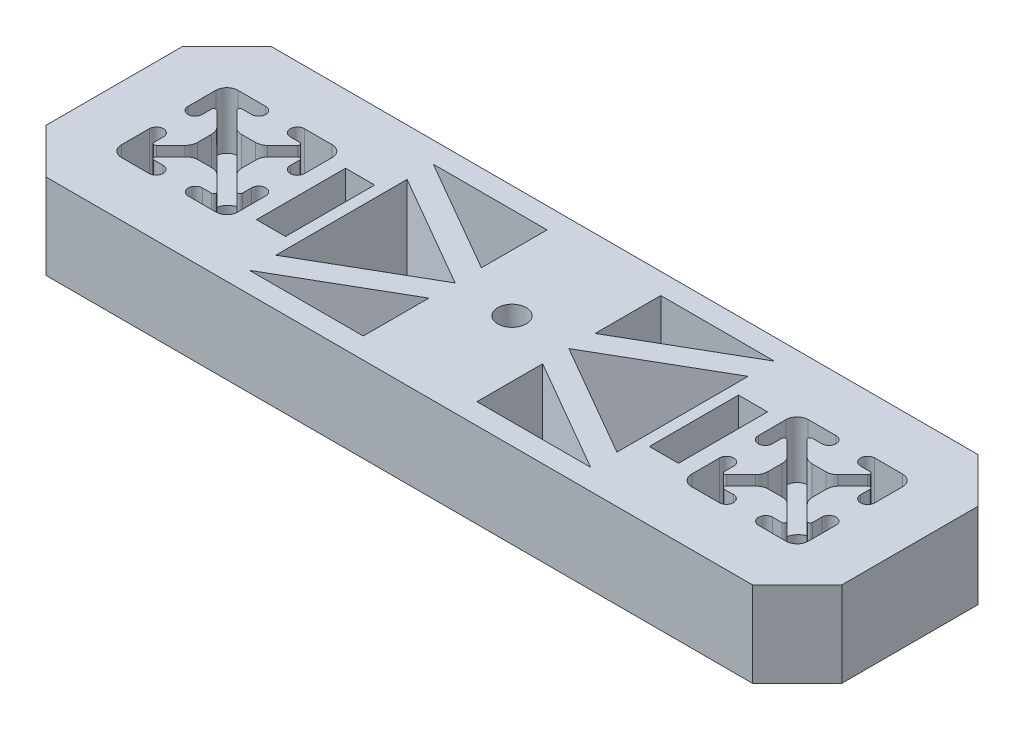
SolidWorks part; units mm, degrees
ref_plane "Front" through (0, 0, 0) normal (0, 0, 1) x (1, 0, 0)
ref_plane "Top" through (0, 0, 0) normal (0, 1, 0) x (1, 0, 0)
ref_plane "Right" through (0, 0, 0) normal (1, 0, 0) x (0, 0, -1)
sketch "Sketch1" plane through (0, 0, 0) normal (0, 1, 0) x (1, 0, 0)
  line L1 (0, 0) -> (177.8, 0)
  line L2 (0, 0) -> (0, 50.4)
  line L3 (0, 50.4) -> (177.8, 50.4)
  line L4 (177.8, 0) -> (177.8, 50.4)
  dimension "D1" = 177.8
  dimension "D2" = 50.4
extrude "Boss-Extrude1" add sketch "Sketch1" along normal blind 6.35
sketch "Sketch2" plane through (0, 6.35, 0) normal (0, 1, 0) x (1, 0, 0)
  line L0 (37.6996, 29.52) -> (37.6996, 35.7372) construction
  line L1 (35.7368, 37.7) -> (29.5196, 37.7) construction
  line L2 (29.5196, 35.56) -> (31.619, 35.56) construction
  line L3 (32.3326, 33.8353) -> (28.9966, 30.504) construction
  line L4 (26.7566, 29.5771) -> (23.643, 29.5771) construction
  line L5 (21.403, 30.504) -> (18.067, 33.8353) construction
  line L6 (18.7806, 35.56) -> (20.88, 35.56) construction
  line L7 (20.88, 37.7) -> (14.6628, 37.7) construction
  line L8 (12.7, 35.7372) -> (12.7, 29.52) construction
  line L9 (14.84, 29.52) -> (14.84, 31.5965) construction
  line L10 (16.5637, 32.3112) -> (19.7659, 29.1135) construction
  line L11 (20.743, 26.7568) -> (20.743, 23.6432) construction
  line L12 (19.7659, 21.2865) -> (16.5637, 18.0888) construction
  line L13 (14.84, 18.8035) -> (14.84, 20.88) construction
  line L14 (12.7, 20.88) -> (12.7, 14.6628) construction
  line L15 (14.6628, 12.7) -> (20.8121, 12.7) construction
  line L16 (20.8121, 14.84) -> (18.7806, 14.84) construction
  line L17 (18.067, 16.5647) -> (21.403, 19.896) construction
  line L18 (23.643, 20.8229) -> (26.7566, 20.8229) construction
  line L19 (28.9966, 19.896) -> (32.3326, 16.5647) construction
  line L20 (31.619, 14.84) -> (29.5875, 14.84) construction
  line L21 (29.5875, 12.7) -> (35.7368, 12.7) construction
  line L22 (37.6996, 14.6628) -> (37.6996, 20.88) construction
  line L23 (35.5596, 20.88) -> (35.5596, 18.8035) construction
  line L24 (33.8359, 18.0888) -> (30.6337, 21.2865) construction
  line L25 (29.6566, 23.6432) -> (29.6566, 26.7568) construction
  line L26 (30.6337, 29.1135) -> (33.8359, 32.3112) construction
  line L27 (35.5596, 31.5965) -> (35.5596, 29.52) construction
  line L28 (0, 50.4) -> (0, 0) construction
  line L29 (177.8, 50.4) -> (0, 50.4) construction
  line L30 (0, 0) -> (177.8, 0) construction
  line L31 (88.9, 50.4) -> (88.9, 0) construction
  line L32 (142.2404, 31.5965) -> (142.2404, 29.52) construction
  line L33 (147.1663, 29.1135) -> (143.9641, 32.3112) construction
  line L34 (148.1434, 23.6432) -> (148.1434, 26.7568) construction
  line L35 (143.9641, 18.0888) -> (147.1663, 21.2865) construction
  line L36 (142.2404, 20.88) -> (142.2404, 18.8035) construction
  line L37 (140.1004, 14.6628) -> (140.1004, 20.88) construction
  line L38 (148.2125, 12.7) -> (142.0632, 12.7) construction
  line L39 (146.181, 14.84) -> (148.2125, 14.84) construction
  line L40 (148.8034, 19.896) -> (145.4674, 16.5647) construction
  line L41 (154.157, 20.8229) -> (151.0434, 20.8229) construction
  line L42 (159.733, 16.5647) -> (156.397, 19.896) construction
  line L43 (156.9879, 14.84) -> (159.0194, 14.84) construction
  line L44 (163.1372, 12.7) -> (156.9879, 12.7) construction
  line L45 (165.1, 20.88) -> (165.1, 14.6628) construction
  line L46 (162.96, 18.8035) -> (162.96, 20.88) construction
  line L47 (158.0341, 21.2865) -> (161.2363, 18.0888) construction
  line L48 (157.057, 26.7568) -> (157.057, 23.6432) construction
  line L49 (161.2363, 32.3112) -> (158.0341, 29.1135) construction
  line L50 (162.96, 29.52) -> (162.96, 31.5965) construction
  line L51 (165.1, 35.7372) -> (165.1, 29.52) construction
  line L52 (156.92, 37.7) -> (163.1372, 37.7) construction
  line L53 (159.0194, 35.56) -> (156.92, 35.56) construction
  line L54 (156.397, 30.504) -> (159.733, 33.8353) construction
  line L55 (151.0434, 29.5771) -> (154.157, 29.5771) construction
  line L56 (145.4674, 33.8353) -> (148.8034, 30.504) construction
  line L57 (148.2804, 35.56) -> (146.181, 35.56) construction
  line L58 (142.0632, 37.7) -> (148.2804, 37.7) construction
  line L59 (140.1004, 29.52) -> (140.1004, 35.7372) construction
  line L60 (38.2076, 29.52) -> (38.2076, 35.7372)
  line L62 (0, 50.4) -> (0, 0)
  line L63 (0, 0) -> (177.8, 0)
  line L64 (177.8, 50.4) -> (177.8, 0)
  line L65 (35.7368, 38.208) -> (29.5196, 38.208)
  line L66 (29.5196, 35.052) -> (31.619, 35.052)
  line L67 (31.9737, 34.1948) -> (28.6376, 30.8635)
  line L68 (26.7566, 30.0851) -> (23.643, 30.0851)
  line L69 (21.762, 30.8635) -> (18.4259, 34.1948)
  line L70 (18.7806, 35.052) -> (20.88, 35.052)
  line L71 (20.88, 38.208) -> (14.6628, 38.208)
  line L72 (12.192, 35.7372) -> (12.192, 29.52)
  line L73 (15.348, 29.52) -> (15.348, 31.5965)
  line L74 (16.2047, 31.9517) -> (19.4069, 28.7541)
  line L75 (20.235, 26.7568) -> (20.235, 23.6432)
  line L76 (19.4069, 21.6459) -> (16.2047, 18.4483)
  line L77 (15.348, 18.8035) -> (15.348, 20.88)
  line L78 (12.192, 20.88) -> (12.192, 14.6628)
  line L79 (14.6628, 12.192) -> (20.8121, 12.192)
  line L80 (20.8121, 15.348) -> (18.7806, 15.348)
  line L81 (18.4259, 16.2052) -> (21.762, 19.5365)
  line L82 (23.643, 20.3149) -> (26.7566, 20.3149)
  line L83 (28.6376, 19.5365) -> (31.9737, 16.2052)
  line L84 (31.619, 15.348) -> (29.5875, 15.348)
  line L85 (29.5875, 12.192) -> (35.7368, 12.192)
  line L86 (38.2076, 14.6628) -> (38.2076, 20.88)
  line L87 (35.0516, 20.88) -> (35.0516, 18.8035)
  line L88 (34.1949, 18.4483) -> (30.9927, 21.6459)
  line L89 (30.1646, 23.6432) -> (30.1646, 26.7568)
  line L90 (30.9927, 28.7541) -> (34.1949, 31.9517)
  line L91 (35.0516, 31.5965) -> (35.0516, 29.52)
  line L92 (142.7484, 31.5965) -> (142.7484, 29.52)
  line L93 (139.5924, 29.52) -> (139.5924, 35.7372)
  line L94 (142.0632, 38.208) -> (148.2804, 38.208)
  line L95 (148.2804, 35.052) -> (146.181, 35.052)
  line L96 (145.8263, 34.1948) -> (149.1624, 30.8635)
  line L97 (151.0434, 30.0851) -> (154.157, 30.0851)
  line L98 (156.038, 30.8635) -> (159.3741, 34.1948)
  line L99 (159.0194, 35.052) -> (156.92, 35.052)
  line L100 (156.92, 38.208) -> (163.1372, 38.208)
  line L101 (165.608, 35.7372) -> (165.608, 29.52)
  line L102 (162.452, 29.52) -> (162.452, 31.5965)
  line L103 (161.5953, 31.9517) -> (158.3931, 28.7541)
  line L104 (157.565, 26.7568) -> (157.565, 23.6432)
  line L105 (158.3931, 21.6459) -> (161.5953, 18.4483)
  line L106 (162.452, 18.8035) -> (162.452, 20.88)
  line L107 (165.608, 20.88) -> (165.608, 14.6628)
  line L108 (163.1372, 12.192) -> (156.9879, 12.192)
  line L109 (156.9879, 15.348) -> (159.0194, 15.348)
  line L110 (159.3741, 16.2052) -> (156.038, 19.5365)
  line L111 (154.157, 20.3149) -> (151.0434, 20.3149)
  line L112 (149.1624, 19.5365) -> (145.8263, 16.2052)
  line L113 (146.181, 15.348) -> (148.2125, 15.348)
  line L114 (148.2125, 12.192) -> (142.0632, 12.192)
  line L115 (139.5924, 14.6628) -> (139.5924, 20.88)
  line L116 (142.7484, 20.88) -> (142.7484, 18.8035)
  line L117 (143.6051, 18.4483) -> (146.8073, 21.6459)
  line L118 (147.6354, 23.6432) -> (147.6354, 26.7568)
  line L119 (146.8073, 28.7541) -> (143.6051, 31.9517)
  line L120 (177.8, 50.4) -> (0, 50.4)
  arc A1 (37.6996, 35.7372) -> (35.7368, 37.7) centre (35.7368, 35.7372) ccw construction
  arc A2 (29.5196, 37.7) -> (29.5196, 35.56) centre (29.5196, 36.63) ccw construction
  arc A3 (31.619, 35.56) -> (32.3326, 33.8353) centre (31.619, 34.55) cw construction
  arc A4 (28.9966, 30.504) -> (26.7566, 29.5771) centre (26.7566, 32.7471) cw construction
  arc A5 (23.643, 29.5771) -> (21.403, 30.504) centre (23.643, 32.7471) cw construction
  arc A6 (18.067, 33.8353) -> (18.7806, 35.56) centre (18.7806, 34.55) cw construction
  arc A7 (20.88, 35.56) -> (20.88, 37.7) centre (20.88, 36.63) ccw construction
  arc A8 (14.6628, 37.7) -> (12.7, 35.7372) centre (14.6628, 35.7372) ccw construction
  arc A9 (12.7, 29.52) -> (14.84, 29.52) centre (13.77, 29.52) ccw construction
  arc A10 (14.84, 31.5965) -> (16.5637, 32.3112) centre (15.85, 31.5965) cw construction
  arc A11 (19.7659, 29.1135) -> (20.743, 26.7568) centre (17.4126, 26.7568) cw construction
  arc A12 (20.743, 23.6432) -> (19.7659, 21.2865) centre (17.4126, 23.6432) cw construction
  arc A13 (16.5637, 18.0888) -> (14.84, 18.8035) centre (15.85, 18.8035) cw construction
  arc A14 (14.84, 20.88) -> (12.7, 20.88) centre (13.77, 20.88) ccw construction
  arc A15 (12.7, 14.6628) -> (14.6628, 12.7) centre (14.6628, 14.6628) ccw construction
  arc A16 (20.8121, 12.7) -> (20.8121, 14.84) centre (20.8121, 13.77) ccw construction
  arc A17 (18.7806, 14.84) -> (18.067, 16.5647) centre (18.7806, 15.85) cw construction
  arc A18 (21.403, 19.896) -> (23.643, 20.8229) centre (23.643, 17.6529) cw construction
  arc A19 (26.7566, 20.8229) -> (28.9966, 19.896) centre (26.7566, 17.6529) cw construction
  arc A20 (32.3326, 16.5647) -> (31.619, 14.84) centre (31.619, 15.85) cw construction
  arc A21 (29.5875, 14.84) -> (29.5875, 12.7) centre (29.5875, 13.77) ccw construction
  arc A22 (35.7368, 12.7) -> (37.6996, 14.6628) centre (35.7368, 14.6628) ccw construction
  arc A23 (37.6996, 20.88) -> (35.5596, 20.88) centre (36.6296, 20.88) ccw construction
  arc A24 (35.5596, 18.8035) -> (33.8359, 18.0888) centre (34.5496, 18.8035) cw construction
  arc A25 (30.6337, 21.2865) -> (29.6566, 23.6432) centre (32.987, 23.6432) cw construction
  arc A26 (29.6566, 26.7568) -> (30.6337, 29.1135) centre (32.987, 26.7568) cw construction
  arc A27 (33.8359, 32.3112) -> (35.5596, 31.5965) centre (34.5496, 31.5965) cw construction
  arc A28 (35.5596, 29.52) -> (37.6996, 29.52) centre (36.6296, 29.52) ccw construction
  arc A29 (142.2404, 29.52) -> (140.1004, 29.52) centre (141.1704, 29.52) cw construction
  arc A30 (143.9641, 32.3112) -> (142.2404, 31.5965) centre (143.2504, 31.5965) ccw construction
  arc A31 (148.1434, 26.7568) -> (147.1663, 29.1135) centre (144.813, 26.7568) ccw construction
  arc A32 (147.1663, 21.2865) -> (148.1434, 23.6432) centre (144.813, 23.6432) ccw construction
  arc A33 (142.2404, 18.8035) -> (143.9641, 18.0888) centre (143.2504, 18.8035) ccw construction
  arc A34 (140.1004, 20.88) -> (142.2404, 20.88) centre (141.1704, 20.88) cw construction
  arc A35 (142.0632, 12.7) -> (140.1004, 14.6628) centre (142.0632, 14.6628) cw construction
  arc A36 (148.2125, 14.84) -> (148.2125, 12.7) centre (148.2125, 13.77) cw construction
  arc A37 (145.4674, 16.5647) -> (146.181, 14.84) centre (146.181, 15.85) ccw construction
  arc A38 (151.0434, 20.8229) -> (148.8034, 19.896) centre (151.0434, 17.6529) ccw construction
  arc A39 (156.397, 19.896) -> (154.157, 20.8229) centre (154.157, 17.6529) ccw construction
  arc A40 (159.0194, 14.84) -> (159.733, 16.5647) centre (159.0194, 15.85) ccw construction
  arc A41 (156.9879, 12.7) -> (156.9879, 14.84) centre (156.9879, 13.77) cw construction
  arc A42 (165.1, 14.6628) -> (163.1372, 12.7) centre (163.1372, 14.6628) cw construction
  arc A43 (162.96, 20.88) -> (165.1, 20.88) centre (164.03, 20.88) cw construction
  arc A44 (161.2363, 18.0888) -> (162.96, 18.8035) centre (161.95, 18.8035) ccw construction
  arc A45 (157.057, 23.6432) -> (158.0341, 21.2865) centre (160.3874, 23.6432) ccw construction
  arc A46 (158.0341, 29.1135) -> (157.057, 26.7568) centre (160.3874, 26.7568) ccw construction
  arc A47 (162.96, 31.5965) -> (161.2363, 32.3112) centre (161.95, 31.5965) ccw construction
  arc A48 (165.1, 29.52) -> (162.96, 29.52) centre (164.03, 29.52) cw construction
  arc A49 (163.1372, 37.7) -> (165.1, 35.7372) centre (163.1372, 35.7372) cw construction
  arc A50 (156.92, 35.56) -> (156.92, 37.7) centre (156.92, 36.63) cw construction
  arc A51 (159.733, 33.8353) -> (159.0194, 35.56) centre (159.0194, 34.55) ccw construction
  arc A52 (154.157, 29.5771) -> (156.397, 30.504) centre (154.157, 32.7471) ccw construction
  arc A53 (148.8034, 30.504) -> (151.0434, 29.5771) centre (151.0434, 32.7471) ccw construction
  arc A54 (146.181, 35.56) -> (145.4674, 33.8353) centre (146.181, 34.55) ccw construction
  arc A55 (148.2804, 37.7) -> (148.2804, 35.56) centre (148.2804, 36.63) cw construction
  arc A56 (140.1004, 35.7372) -> (142.0632, 37.7) centre (142.0632, 35.7372) cw construction
  arc A58 (38.2076, 35.7372) -> (35.7368, 38.208) centre (35.7368, 35.7372) ccw
  arc A59 (29.5196, 38.208) -> (29.5196, 35.052) centre (29.5196, 36.63) ccw
  arc A60 (31.619, 35.052) -> (31.9737, 34.1948) centre (31.619, 34.55) cw
  arc A61 (28.6376, 30.8635) -> (26.7566, 30.0851) centre (26.7566, 32.7471) cw
  arc A62 (23.643, 30.0851) -> (21.762, 30.8635) centre (23.643, 32.7471) cw
  arc A63 (18.4259, 34.1948) -> (18.7806, 35.052) centre (18.7806, 34.55) cw
  arc A64 (20.88, 35.052) -> (20.88, 38.208) centre (20.88, 36.63) ccw
  arc A65 (14.6628, 38.208) -> (12.192, 35.7372) centre (14.6628, 35.7372) ccw
  arc A66 (12.192, 29.52) -> (15.348, 29.52) centre (13.77, 29.52) ccw
  arc A67 (15.348, 31.5965) -> (16.2047, 31.9517) centre (15.85, 31.5965) cw
  arc A68 (19.4069, 28.7541) -> (20.235, 26.7568) centre (17.4126, 26.7568) cw
  arc A69 (20.235, 23.6432) -> (19.4069, 21.6459) centre (17.4126, 23.6432) cw
  arc A70 (16.2047, 18.4483) -> (15.348, 18.8035) centre (15.85, 18.8035) cw
  arc A71 (15.348, 20.88) -> (12.192, 20.88) centre (13.77, 20.88) ccw
  arc A72 (12.192, 14.6628) -> (14.6628, 12.192) centre (14.6628, 14.6628) ccw
  arc A73 (20.8121, 12.192) -> (20.8121, 15.348) centre (20.8121, 13.77) ccw
  arc A74 (18.7806, 15.348) -> (18.4259, 16.2052) centre (18.7806, 15.85) cw
  arc A75 (21.762, 19.5365) -> (23.643, 20.3149) centre (23.643, 17.6529) cw
  arc A76 (26.7566, 20.3149) -> (28.6376, 19.5365) centre (26.7566, 17.6529) cw
  arc A77 (31.9737, 16.2052) -> (31.619, 15.348) centre (31.619, 15.85) cw
  arc A78 (29.5875, 15.348) -> (29.5875, 12.192) centre (29.5875, 13.77) ccw
  arc A79 (35.7368, 12.192) -> (38.2076, 14.6628) centre (35.7368, 14.6628) ccw
  arc A80 (38.2076, 20.88) -> (35.0516, 20.88) centre (36.6296, 20.88) ccw
  arc A81 (35.0516, 18.8035) -> (34.1949, 18.4483) centre (34.5496, 18.8035) cw
  arc A82 (30.9927, 21.6459) -> (30.1646, 23.6432) centre (32.987, 23.6432) cw
  arc A83 (30.1646, 26.7568) -> (30.9927, 28.7541) centre (32.987, 26.7568) cw
  arc A84 (34.1949, 31.9517) -> (35.0516, 31.5965) centre (34.5496, 31.5965) cw
  arc A85 (35.0516, 29.52) -> (38.2076, 29.52) centre (36.6296, 29.52) ccw
  arc A86 (142.7484, 29.52) -> (139.5924, 29.52) centre (141.1704, 29.52) cw
  arc A87 (139.5924, 35.7372) -> (142.0632, 38.208) centre (142.0632, 35.7372) cw
  arc A88 (148.2804, 38.208) -> (148.2804, 35.052) centre (148.2804, 36.63) cw
  arc A89 (146.181, 35.052) -> (145.8263, 34.1948) centre (146.181, 34.55) ccw
  arc A90 (149.1624, 30.8635) -> (151.0434, 30.0851) centre (151.0434, 32.7471) ccw
  arc A91 (154.157, 30.0851) -> (156.038, 30.8635) centre (154.157, 32.7471) ccw
  arc A92 (159.3741, 34.1948) -> (159.0194, 35.052) centre (159.0194, 34.55) ccw
  arc A93 (156.92, 35.052) -> (156.92, 38.208) centre (156.92, 36.63) cw
  arc A94 (163.1372, 38.208) -> (165.608, 35.7372) centre (163.1372, 35.7372) cw
  arc A95 (165.608, 29.52) -> (162.452, 29.52) centre (164.03, 29.52) cw
  arc A96 (162.452, 31.5965) -> (161.5953, 31.9517) centre (161.95, 31.5965) ccw
  arc A97 (158.3931, 28.7541) -> (157.565, 26.7568) centre (160.3874, 26.7568) ccw
  arc A98 (157.565, 23.6432) -> (158.3931, 21.6459) centre (160.3874, 23.6432) ccw
  arc A99 (161.5953, 18.4483) -> (162.452, 18.8035) centre (161.95, 18.8035) ccw
  arc A100 (162.452, 20.88) -> (165.608, 20.88) centre (164.03, 20.88) cw
  arc A101 (165.608, 14.6628) -> (163.1372, 12.192) centre (163.1372, 14.6628) cw
  arc A102 (156.9879, 12.192) -> (156.9879, 15.348) centre (156.9879, 13.77) cw
  arc A103 (159.0194, 15.348) -> (159.3741, 16.2052) centre (159.0194, 15.85) ccw
  arc A104 (156.038, 19.5365) -> (154.157, 20.3149) centre (154.157, 17.6529) ccw
  arc A105 (151.0434, 20.3149) -> (149.1624, 19.5365) centre (151.0434, 17.6529) ccw
  arc A106 (145.8263, 16.2052) -> (146.181, 15.348) centre (146.181, 15.85) ccw
  arc A107 (148.2125, 15.348) -> (148.2125, 12.192) centre (148.2125, 13.77) cw
  arc A108 (142.0632, 12.192) -> (139.5924, 14.6628) centre (142.0632, 14.6628) cw
  arc A109 (139.5924, 20.88) -> (142.7484, 20.88) centre (141.1704, 20.88) cw
  arc A110 (142.7484, 18.8035) -> (143.6051, 18.4483) centre (143.2504, 18.8035) ccw
  arc A111 (146.8073, 21.6459) -> (147.6354, 23.6432) centre (144.813, 23.6432) ccw
  arc A112 (147.6354, 26.7568) -> (146.8073, 28.7541) centre (144.813, 26.7568) ccw
  arc A113 (143.6051, 31.9517) -> (142.7484, 31.5965) centre (143.2504, 31.5965) ccw
  dimension "D2" = 1.07
  dimension "D3" = 3.17
  dimension "D4" = 3.3305
  dimension "D8" = 1.9628
  dimension "D9" = 1.01
  dimension "D5" = 12.7
  dimension "D6" = 12.7
  dimension "D7" = 12.7
  dimension "D10" = 16.5637
  dimension "D12" = 0.508
  dimension "D13" = 0.508
extrude "Boss-Extrude2" add sketch "Sketch2" along normal blind 12.7
sketch "Sketch3" plane through (0, 19.05, 0) normal (0, 1, 0) x (1, 0, 0)
  line L0 (177.8, 50.4) -> (0, 50.4) construction
  line L1 (0, 50.4) -> (0, 0) construction
  circle A0 centre (88.9, 25.2) radius 3.175
  point P4 (88.9, 50.4)
  point P7 (0, 25.2)
  dimension "D1" = 6.35
extrude "Cut-Extrude1" cut sketch "Sketch3" against normal through all
sketch "Sketch4" plane through (0, 19.05, 0) normal (0, 1, 0) x (1, 0, 0)
  line L0 (50.8, 45.7306) -> (76.2, 45.7306)
  line L1 (76.2, 45.7306) -> (76.2, 31.0659)
  line L2 (76.2, 31.0659) -> (50.8, 45.7306)
  line L3 (76.2, 19.3341) -> (76.2, 4.6694)
  line L4 (76.2, 4.6694) -> (50.8, 4.6694)
  line L5 (50.8, 4.6694) -> (76.2, 19.3341)
  line L6 (50.8, 39.8647) -> (50.8, 10.5353)
  line L7 (50.8, 10.5353) -> (76.2, 25.2)
  line L8 (76.2, 25.2) -> (50.8, 39.8647)
  line L9 (0, 50.4) -> (0, 0) construction
  line L10 (88.9, 50.4) -> (88.9, 0) construction
  line L11 (177.8, 50.4) -> (0, 50.4) construction
  line L12 (0, 0) -> (177.8, 0) construction
  line L13 (101.6, 25.2) -> (127, 39.8647)
  line L14 (127, 10.5353) -> (101.6, 25.2)
  line L15 (127, 39.8647) -> (127, 10.5353)
  line L16 (127, 4.6694) -> (101.6, 19.3341)
  line L17 (101.6, 4.6694) -> (127, 4.6694)
  line L18 (101.6, 19.3341) -> (101.6, 4.6694)
  line L19 (101.6, 31.0659) -> (127, 45.7306)
  line L20 (101.6, 45.7306) -> (101.6, 31.0659)
  line L21 (127, 45.7306) -> (101.6, 45.7306)
  point P18 (88.9, 25.2)
  dimension "D1" = 25.4
  dimension "D2" = 25.4
  dimension "D3" = 50.8
  dimension "D4" = 5.08
  dimension "D5" = 5.08
  dimension "D7" = 60
extrude "Cut-Extrude2" cut sketch "Sketch4" against normal through all
chamfer "Chamfer1" distance 10 angle 45 4 edges at (177.8, 9.525, -50.4) (177.8, 9.525, 0) (0, 9.525, 0) (0, 9.525, -50.4)
sketch "Sketch5" plane through (0, 19.05, 0) normal (0, 1, 0) x (1, 0, 0)
  line L0 (0, 40.4) -> (0, 10) construction
  line L1 (41.7636, 35.15) -> (48.2636, 35.15)
  line L2 (41.7636, 35.15) -> (41.7636, 15.25)
  line L3 (41.7636, 15.25) -> (48.2636, 15.25)
  line L4 (48.2636, 35.15) -> (48.2636, 15.25)
  line L5 (38.2076, 29.52) -> (38.2076, 35.7372) construction
  point P6 (0, 25.2)
  point P7 (48.2636, 25.2)
  dimension "D1" = 6.5
  dimension "D2" = 19.9
  dimension "D3" = 3.556
extrude "Cut-Extrude3" cut sketch "Sketch5" against normal blind 10.2
sketch "Sketch6" plane through (0, 8.85, 0) normal (0, 1, 0) x (1, 0, 0)
  line L0 (48.2636, 15.25) -> (48.2636, 35.15) construction
  line L1 (41.7636, 35.15) -> (48.2636, 35.15)
  line L2 (41.7636, 35.15) -> (41.7636, 30.578)
  line L3 (41.7636, 30.578) -> (48.2636, 30.578)
  line L4 (48.2636, 35.15) -> (48.2636, 30.578)
  line L5 (41.7636, 35.15) -> (41.7636, 15.25) construction
  line L6 (48.2636, 15.25) -> (48.2636, 35.15) construction
  line L7 (41.7636, 27.486) -> (48.2636, 27.486)
  line L8 (41.7636, 27.486) -> (41.7636, 22.914)
  line L9 (41.7636, 22.914) -> (48.2636, 22.914)
  line L10 (48.2636, 27.486) -> (48.2636, 22.914)
  line L12 (41.7636, 15.25) -> (48.2636, 15.25)
  line L13 (41.7636, 15.25) -> (41.7636, 19.822)
  line L14 (41.7636, 19.822) -> (48.2636, 19.822)
  line L15 (48.2636, 15.25) -> (48.2636, 19.822)
  line L16 (41.7636, 25.2) -> (0, 25.2) construction
  line L17 (0, 40.4) -> (0, 10) construction
  dimension "D1" = 4.572
extrude "Cut-Extrude4" cut sketch "Sketch6" against normal through all
ref_plane "Plane1" through (88.9, 0, 0) normal (-1, 0, 0) x (0, 0, 1)
mirror "Mirror1" about plane through (88.9, 0, 0) normal (-1, 0, 0) of "Cut-Extrude4", "Cut-Extrude3"
sketch "Sketch7" plane through (0, 19.05, 0) normal (0, 1, 0) x (1, 0, 0)
  line L0 (26.7566, 30.0851) -> (23.643, 30.0851) construction
  line L1 (30.1646, 23.6432) -> (30.1646, 26.7568) construction
  circle A0 centre (25.3386, 25.2591) radius 3.175
  dimension "D3" = 6.35
  dimension "D1" = 4.826
  dimension "D2" = 4.826
extrude "Cut-Extrude5" cut sketch "Sketch7" against normal through all both and the other way through all
sketch "Sketch8" plane through (0, 6.35, 0) normal (0, 1, 0) x (1, 0, 0)
  line L0 (154.157, 30.0851) -> (151.0434, 30.0851) construction
  line L1 (157.565, 23.6432) -> (157.565, 26.7568) construction
  circle A0 centre (152.739, 25.2591) radius 3.175
  dimension "D3" = 6.35
  dimension "D1" = 4.826
  dimension "D2" = 4.826
extrude "Cut-Extrude6" cut sketch "Sketch8" against normal through all both and the other way through all
